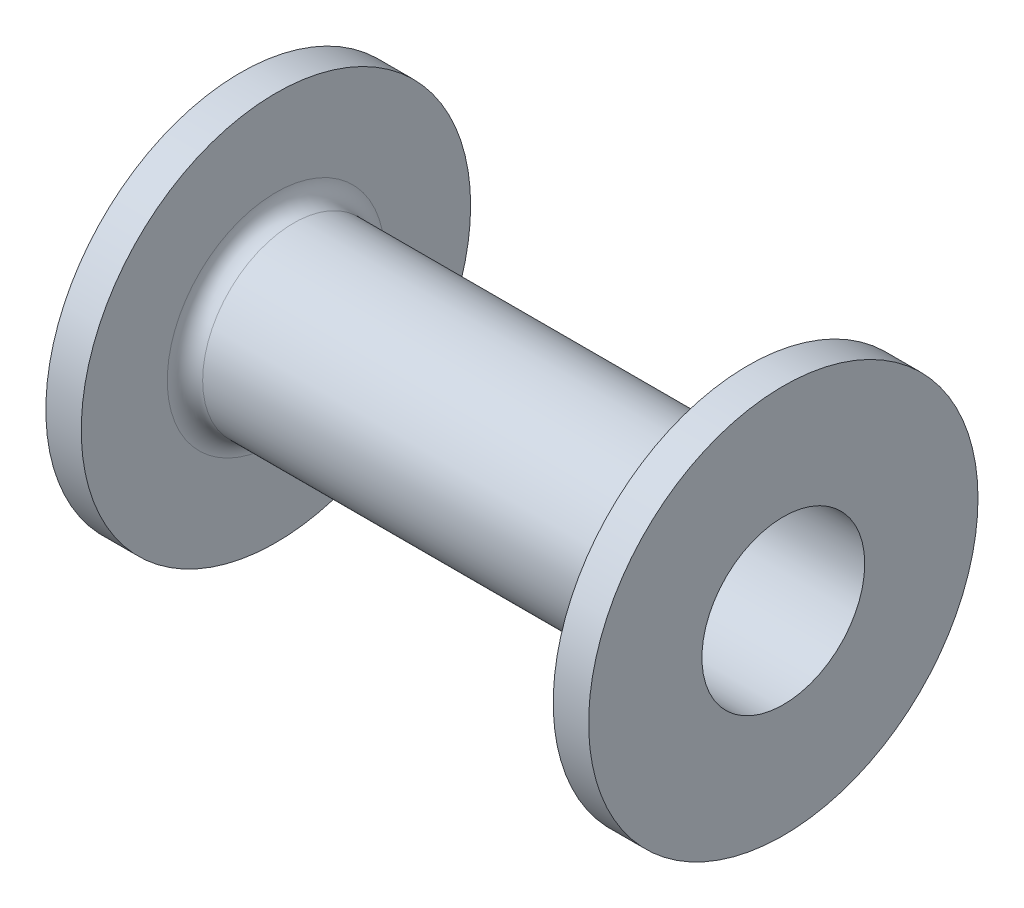
SolidWorks part; units mm, degrees
other "Marcação1"
sketch "Esboço1" plane through (0, 14, -14) normal (-0.9571, 0.2145, -0.1948) x (-0.2106, -0.053, 0.9761)
ref_plane "Front Plane" through (0, 0, 0) normal (0, 0, 1) x (1, 0, 0)
ref_plane "Top Plane" through (0, 0, 0) normal (0, 1, 0) x (1, 0, 0)
ref_plane "Right Plane" through (0, 0, 0) normal (1, 0, 0) x (0, 0, -1)
sketch "Sketch1" plane through (0, 0, 0) normal (0, 0, 1) x (1, 0, 0)
  line L0 (0, 6.9) -> (0, 16.5)
  line L1 (0, 0) -> (-13.4865, 0) construction
  line L2 (0, 16.5) -> (3, 16.5)
  line L3 (3, 16.5) -> (3, 9.21)
  line L4 (3, 6.9) -> (43, 6.9)
  line L5 (4.5, 7.71) -> (41.5, 7.71)
  line L6 (3, 6.9) -> (0, 6.9)
  line L7 (43, 9.21) -> (43, 16.5)
  line L8 (43, 16.5) -> (46, 16.5)
  line L9 (46, 16.5) -> (46, 6.9)
  line L10 (46, 6.9) -> (43, 6.9)
  arc A0 (41.5, 7.71) -> (43, 9.21) centre (41.5, 9.21) ccw
  arc A1 (4.5, 7.71) -> (3, 9.21) centre (4.5, 9.21) cw
  point P17 (3, 7.71)
  dimension "D1" = 13.8
  dimension "D2" = 3
  dimension "D6" = 1.5
  dimension "D3" = 33
  dimension "D4" = 0.81
  dimension "D5" = 40
revolve "Revolve1" add sketch "Sketch1" angle 360 about L1
